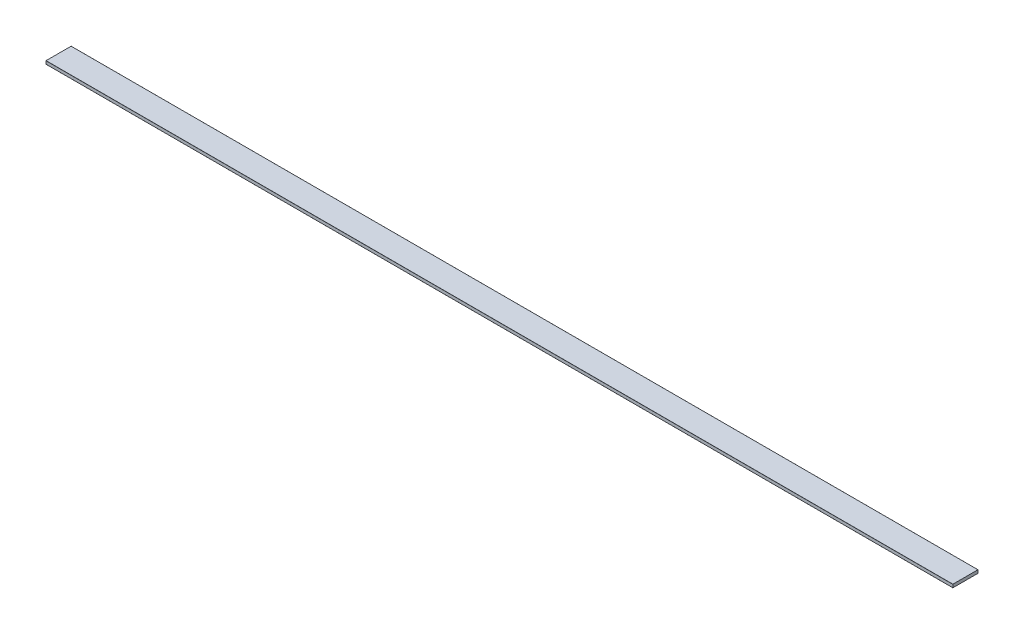
SolidWorks part; units mm, degrees
ref_plane "Front Plane" through (0, 0, 0) normal (0, 0, 1) x (1, 0, 0)
ref_plane "Top Plane" through (0, 0, 0) normal (0, 1, 0) x (1, 0, 0)
ref_plane "Right Plane" through (0, 0, 0) normal (1, 0, 0) x (0, 0, -1)
sketch "Sketch1" plane through (0, 0, 0) normal (0, 1, 0) x (1, 0, 0)
  line L1 (457.2, -12.7) -> (-457.2, -12.7)
  line L2 (457.2, -12.7) -> (457.2, 12.7)
  line L3 (457.2, 12.7) -> (-457.2, 12.7)
  line L4 (-457.2, -12.7) -> (-457.2, 12.7)
  line L5 (457.2, -12.7) -> (-457.2, 12.7) construction
  line L6 (457.2, 12.7) -> (-457.2, -12.7) construction
  point P0 (0, 0)
  dimension "Length" = 914.4
  dimension "Width" = 25.4
sketch "Sketch2" plane through (0, 0, 0) normal (1, 0, 0) x (0, 0, -1)
  line L0 (12.7, 1.5875) -> (12.7, -1.5875) construction
  point P2 (12.7, 0)
  dimension "Thickness" = 3.175
sketch "Sketch3" plane through (0, 0, 0) normal (0, 1, 0) x (1, 0, 0)
  line L1 (-457.2, 12.7) -> (457.2, 12.7)
  line L2 (-457.2, 12.7) -> (-457.2, -12.7)
  line L3 (-457.2, -12.7) -> (457.2, -12.7)
  line L4 (457.2, 12.7) -> (457.2, -12.7)
extrude "Boss-Extrude1" add sketch "Sketch3" against normal up to vertex (1.5875 mm away) and the other way up to vertex (1.5875 mm away) up to point (0, -1.5875, -12.7) other way up to point (0, 1.5875, -12.7)
fillet "Fillet1" radius 0.1048 4 edges at (0, -1.5875, 12.7) (0, -1.5875, -12.7) (0, 1.5875, -12.7) (0, 1.5875, 12.7)
equation "\"D1@Fillet1\" = \"Thickness@Sketch2\" * .033"
